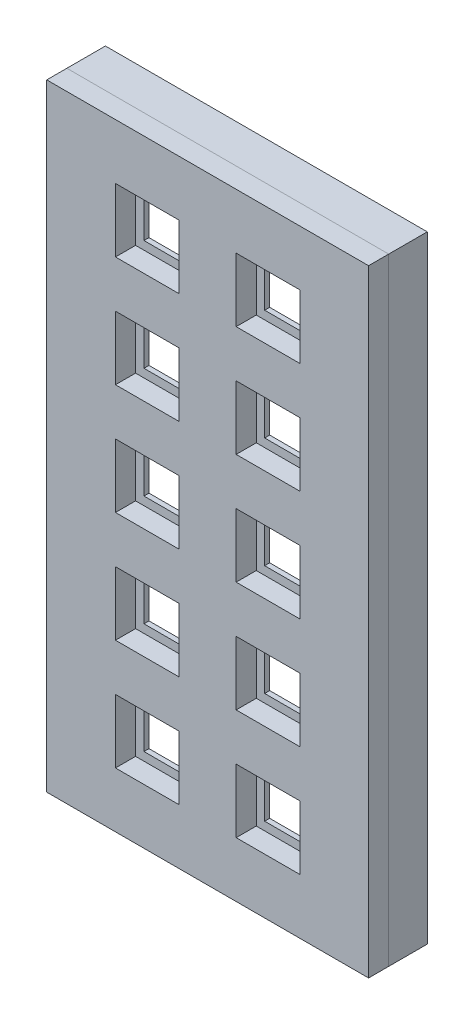
SolidWorks part; units mm, degrees
ref_plane "Front Plane" through (0, 0, 0) normal (1, 0, 0) x (0, 1, 0)
ref_plane "Top Plane" through (0, 0, 0) normal (0, 0, 1) x (0, 1, 0)
ref_plane "Right Plane" through (0, 0, 0) normal (0, 1, 0) x (-1, 0, 0)
sketch "Sketch1" plane through (0, 0, 0) normal (0, 0, 1) x (0, 1, 0)
  line L1 (0, 0) -> (184, 0)
  line L2 (0, 0) -> (0, 96)
  line L3 (0, 96) -> (184, 96)
  line L4 (184, 0) -> (184, 96)
  dimension "D1" = 96
  dimension "D2" = 184
extrude "Boss-Extrude1" add sketch "Sketch1" along normal blind 1.5
sketch "Sketch2" plane through (0, 0, 1.5) normal (0, 0, 1) x (1, 0, 0)
  line L0 (-48, 184) -> (-48, 0) construction
  line L1 (0, 184) -> (-96, 184) construction
  line L2 (-96, 0) -> (0, 0) construction
  line L3 (0, 92) -> (-96, 92) construction
  line L4 (0, 0) -> (0, 184) construction
  line L5 (-96, 184) -> (-96, 0) construction
  line L6 (-73, 66) -> (-59, 66)
  line L7 (-73, 99) -> (-59, 99)
  line L8 (-73, 99) -> (-73, 85)
  line L9 (-73, 85) -> (-59, 85)
  line L10 (-59, 99) -> (-59, 85)
  line L11 (-73, 66) -> (-73, 52)
  line L12 (-73, 52) -> (-59, 52)
  line L13 (-59, 66) -> (-59, 52)
  line L14 (-73, 33) -> (-59, 33)
  line L15 (-73, 33) -> (-73, 19)
  line L16 (-73, 19) -> (-59, 19)
  line L17 (-59, 33) -> (-59, 19)
  line L26 (-73, 132) -> (-59, 132)
  line L27 (-73, 132) -> (-73, 118)
  line L28 (-73, 118) -> (-59, 118)
  line L29 (-59, 132) -> (-59, 118)
  line L38 (-73, 165) -> (-59, 165)
  line L39 (-73, 165) -> (-73, 151)
  line L40 (-73, 151) -> (-59, 151)
  line L41 (-59, 165) -> (-59, 151)
  line L42 (-23, 99) -> (-23, 85)
  line L43 (-23, 99) -> (-37, 99)
  line L44 (-37, 99) -> (-37, 85)
  line L45 (-23, 85) -> (-37, 85)
  line L46 (-37, 66) -> (-37, 52)
  line L47 (-23, 52) -> (-37, 52)
  line L48 (-23, 66) -> (-23, 52)
  line L49 (-23, 66) -> (-37, 66)
  line L50 (-37, 33) -> (-37, 19)
  line L51 (-23, 19) -> (-37, 19)
  line L52 (-23, 33) -> (-23, 19)
  line L53 (-23, 33) -> (-37, 33)
  line L58 (-37, 165) -> (-37, 151)
  line L59 (-23, 151) -> (-37, 151)
  line L60 (-23, 165) -> (-23, 151)
  line L61 (-23, 165) -> (-37, 165)
  line L62 (-37, 132) -> (-37, 118)
  line L63 (-23, 118) -> (-37, 118)
  line L64 (-23, 132) -> (-23, 118)
  line L65 (-23, 132) -> (-37, 132)
  line L70 (-73, 66) -> (-59, 66) [skipped]
  line L71 (-73, 99) -> (-59, 99) [skipped]
  line L72 (-73, 99) -> (-59, 99) [skipped]
  line L73 (-73, 132) -> (-73, 118) [skipped]
  line L74 (-73, 99) -> (-73, 85) [skipped]
  line L75 (-73, 99) -> (-73, 85) [skipped]
  line L76 (-73, 66) -> (-73, 52) [skipped]
  line L77 (-73, 85) -> (-59, 85) [skipped]
  line L78 (-73, 85) -> (-59, 85) [skipped]
  line L79 (-59, 132) -> (-59, 118) [skipped]
  line L80 (-59, 99) -> (-59, 85) [skipped]
  line L81 (-59, 99) -> (-59, 85) [skipped]
  line L82 (-59, 66) -> (-59, 52) [skipped]
  line L83 (-73, 52) -> (-59, 52) [skipped]
  line L84 (-73, 132) -> (-59, 132) [skipped]
  line L85 (-73, 118) -> (-59, 118) [skipped]
  dimension "D1" = 14
  dimension "D2" = 14
  dimension "D3" = 11
  dimension "D4" = 7
  dimension "D5" = 3
  dimension "D6" = 3
extrude "Cut-Extrude1" cut sketch "Sketch2" against normal blind 1.5
sketch "Sketch3" plane through (0, 0, 1.5) normal (0, 0, 1) x (1, 0, 0)
  line L0 (-73, 151) -> (-59, 151) construction
  line L1 (-59, 151) -> (-59, 165) construction
  line L2 (-59, 165) -> (-73, 165) construction
  line L3 (-73, 165) -> (-73, 151) construction
  line L4 (-96, 0) -> (0, 0)
  line L5 (0, 0) -> (0, 184)
  line L6 (0, 184) -> (-96, 184)
  line L7 (-96, 184) -> (-96, 0)
  line L8 (-96, 0) -> (0, 0)
  line L9 (0, 0) -> (0, 184)
  line L10 (0, 184) -> (-96, 184)
  line L11 (-96, 184) -> (-96, 0)
  line L12 (-73, 151) -> (-59, 151) construction
  line L13 (-59, 151) -> (-59, 165) construction
  line L14 (-59, 165) -> (-73, 165) construction
  line L15 (-73, 165) -> (-73, 151) construction
  line L16 (-75.5, 148.5) -> (-56.5, 148.5)
  line L17 (-56.5, 148.5) -> (-56.5, 167.5)
  line L18 (-56.5, 167.5) -> (-75.5, 167.5)
  line L19 (-75.5, 167.5) -> (-75.5, 148.5)
  line L20 (-20.5, 148.5) -> (-20.5, 167.5)
  line L21 (-20.5, 167.5) -> (-39.5, 167.5)
  line L22 (-39.5, 167.5) -> (-39.5, 148.5)
  line L23 (-39.5, 148.5) -> (-20.5, 148.5)
  line L24 (-20.5, 115.5) -> (-20.5, 134.5)
  line L25 (-20.5, 134.5) -> (-39.5, 134.5)
  line L26 (-39.5, 134.5) -> (-39.5, 115.5)
  line L27 (-39.5, 115.5) -> (-20.5, 115.5)
  line L28 (-20.5, 82.5) -> (-20.5, 101.5)
  line L29 (-20.5, 101.5) -> (-39.5, 101.5)
  line L30 (-39.5, 101.5) -> (-39.5, 82.5)
  line L31 (-39.5, 82.5) -> (-20.5, 82.5)
  line L32 (-20.5, 49.5) -> (-20.5, 68.5)
  line L33 (-20.5, 68.5) -> (-39.5, 68.5)
  line L34 (-39.5, 68.5) -> (-39.5, 49.5)
  line L35 (-39.5, 49.5) -> (-20.5, 49.5)
  line L36 (-20.5, 16.5) -> (-20.5, 35.5)
  line L37 (-20.5, 35.5) -> (-39.5, 35.5)
  line L38 (-39.5, 35.5) -> (-39.5, 16.5)
  line L39 (-39.5, 16.5) -> (-20.5, 16.5)
  line L40 (-56.5, 115.5) -> (-56.5, 134.5)
  line L41 (-56.5, 134.5) -> (-75.5, 134.5)
  line L42 (-75.5, 134.5) -> (-75.5, 115.5)
  line L43 (-75.5, 115.5) -> (-56.5, 115.5)
  line L44 (-56.5, 82.5) -> (-56.5, 101.5)
  line L45 (-56.5, 101.5) -> (-75.5, 101.5)
  line L46 (-75.5, 101.5) -> (-75.5, 82.5)
  line L47 (-75.5, 82.5) -> (-56.5, 82.5)
  line L48 (-56.5, 49.5) -> (-56.5, 68.5)
  line L49 (-56.5, 68.5) -> (-75.5, 68.5)
  line L50 (-75.5, 68.5) -> (-75.5, 49.5)
  line L51 (-75.5, 49.5) -> (-56.5, 49.5)
  line L52 (-56.5, 16.5) -> (-56.5, 35.5)
  line L53 (-56.5, 35.5) -> (-75.5, 35.5)
  line L54 (-75.5, 35.5) -> (-75.5, 16.5)
  line L55 (-75.5, 16.5) -> (-56.5, 16.5)
  dimension "D3" = 2
  dimension "D1" = 0
  dimension "D2" = 2.5
  dimension "D4" = 5
extrude "up-cover" add sketch "Sketch3" along normal blind 6 separate body
sketch "Sketch4" plane through (0, 0, 0) normal (0, 0, -1) x (1, 0, 0)
  line L0 (-3, -3) -> (-93, -3)
  line L1 (-93, -3) -> (-93, -181)
  line L2 (-93, -181) -> (-3, -181)
  line L3 (-3, -181) -> (-3, -3)
  line L4 (0, 0) -> (-96, 0)
  line L5 (-96, 0) -> (-96, -184)
  line L6 (-96, -184) -> (0, -184)
  line L7 (0, -184) -> (0, 0)
  line L8 (0, 0) -> (-96, 0)
  line L9 (-96, 0) -> (-96, -184)
  line L10 (-96, -184) -> (0, -184)
  line L11 (0, -184) -> (0, 0)
  dimension "D1" = 0
  dimension "D2" = 3
extrude "Boss-Extrude3" add sketch "Sketch4" along normal blind 10
